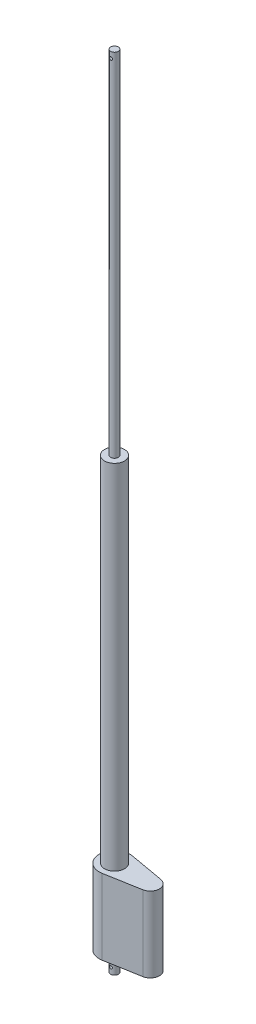
SolidWorks part; units mm, degrees
ref_plane "Front" through (0, 0, 0) normal (0, 0, 1) x (1, 0, 0)
ref_plane "Top" through (0, 0, 0) normal (0, 1, 0) x (1, 0, 0)
ref_plane "Right" through (0, 0, 0) normal (1, 0, 0) x (0, 0, -1)
sketch "Sketch7" plane through (0, 0, 0) normal (1, 0, 0) x (0, 0, -1)
  line L1 (-20, 17) -> (-20, 115)
  line L4 (-13, 575) -> (-5, 575)
  line L5 (-5, 575) -> (-5, 1033)
  line L6 (-5, 1033) -> (0, 1033)
  line L7 (0, 1033) -> (0, -8)
  line L9 (-5, -8) -> (0, -8)
  line L10 (-13, 575) -> (-13, 115)
  line L11 (-13, 115) -> (-20, 115)
  line L12 (-5, -8) -> (-5, 17)
  line L13 (-5, 17) -> (-20, 17)
  point P11 (0, 0)
  point P12 (0, 1025)
  point P13 (0, 600)
  dimension "D1" = 8
  dimension "D2" = 8
  dimension "D3" = 98
  dimension "D5" = 25
  dimension "D4" = 600
  dimension "D7" = 13
  dimension "D8" = 20
  dimension "D11" = 5
  dimension "D9" = 25
  dimension "D10" = 5
  dimension "D6" = 450
revolve "Revolve2" add sketch "Sketch7" angle 360 about L7
sketch "Sketch8" plane through (0, 0, 0) normal (0, 0, 1) x (1, 0, 0)
  line L0 (-5, -8) -> (5, -8) construction
  line L2 (0, 1033) -> (0, 1025) construction
  line L3 (5, 1033) -> (-5, 1033) construction
  line L4 (-5, -8) -> (5, -8) construction
  line L5 (0, -8) -> (0, 0) construction
  circle A1 centre (0, 1025) radius 2
  circle A2 centre (0, 0) radius 2
  dimension "D2" = 8
  dimension "D1" = 4
  dimension "D4" = 4
  dimension "D3" = 8
extrude "Cut-Extrude2" cut sketch "Sketch8" against normal through all and the other way through all
sketch "Sketch10" plane through (0, 115, 0) normal (0, 1, 0) x (1, 0, 0)
  line L0 (0, 0) -> (46.5567, 0) construction
  line L1 (3.491, 19.693) -> (48.6292, 11.6912)
  line L2 (48.6292, -11.6912) -> (3.491, -19.693)
  circle A1 centre (0, 0) radius 20 construction
  arc A2 (48.6292, 11.6912) -> (48.6292, -11.6912) centre (46.5567, 0) cw
  arc A3 (3.491, 19.693) -> (3.491, -19.693) centre (0, 0) ccw
extrude "Boss-Extrude4" add sketch "Sketch10" against normal up to surface (98 mm away) up to face at (0, 17, 5)
sketch "Sketch11" plane through (0, 0, 0) normal (0, 0, 1) x (1, 0, 0)
  line L0 (0, 1025) -> (0, 0)
equation "\"mountingHoleDistance\"=8"
equation "\"actuatorLength\"= 450"
equation "\"D1@Sketch7\"=\"mountingHoleDistance\""
equation "\"D2@Sketch7\"=\"mountingHoleDistance\""
equation "\"MotorHousingHeight\"= 98"
equation "\"D3@Sketch7\"=\"MotorHousingHeight\""
equation "\"acutatorMinimumLength\"=600"
equation "\"D4@Sketch7\"=\"acutatorMinimumLength\""
equation "\"D3@Sketch8\"=\"mountingHoleDistance\""
equation "\"D2@Sketch8\"=\"mountingHoleDistance\""
equation "\"D6@Sketch7\"= \"actuatorLength\""
